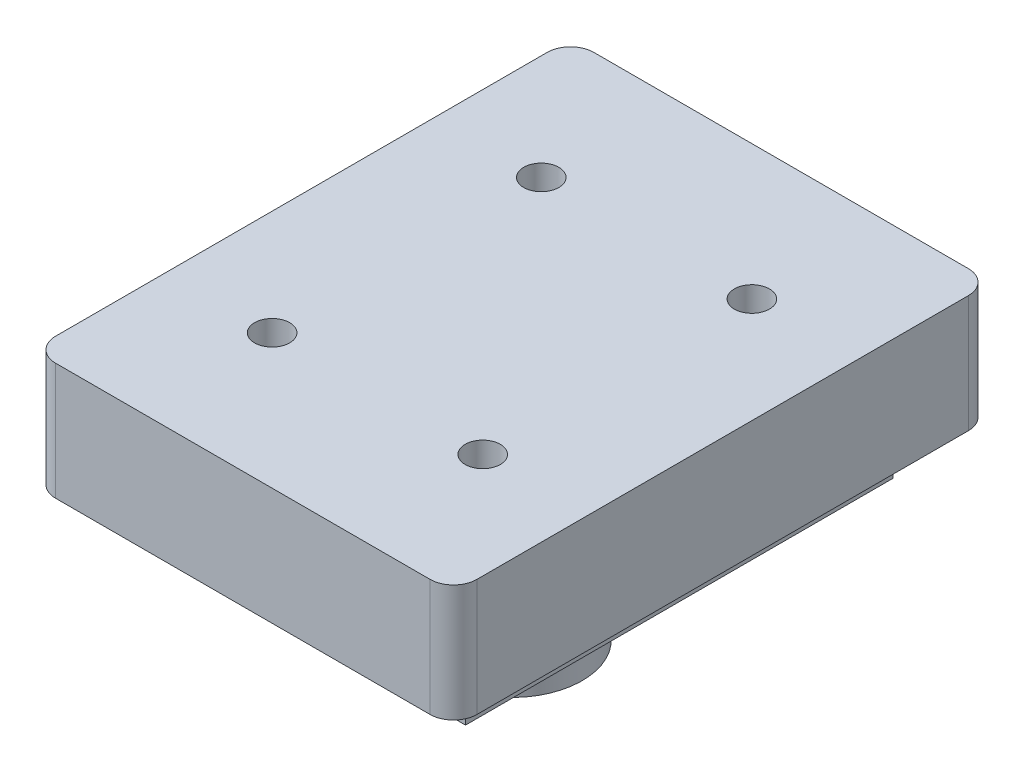
SolidWorks part; units mm, degrees
ref_plane "Front Plane" through (0, 0, 0) normal (0, 0, 1) x (1, 0, 0)
ref_plane "Top Plane" through (0, 0, 0) normal (0, 1, 0) x (1, 0, 0)
ref_plane "Right Plane" through (0, 0, 0) normal (1, 0, 0) x (0, 0, -1)
sketch "Sketch1" plane through (0, 0, 0) normal (0, 1, 0) x (1, 0, 0)
  line L1 (-19.9858, 28.651) -> (25.7342, 28.651)
  line L2 (-19.9858, 28.651) -> (-19.9858, -29.769)
  line L3 (-19.9858, -29.769) -> (25.7342, -29.769)
  line L4 (25.7342, 28.651) -> (25.7342, -29.769)
  dimension "D1" = 58.42
  dimension "D2" = 45.72
extrude "Boss-Extrude1" add sketch "Sketch1" along normal blind 12.7
sketch "Sketch2" plane through (0, 12.7, 0) normal (0, 1, 0) x (1, 0, 0)
  line L1 (25.7342, 28.651) -> (-19.9858, 28.651) construction
  line L3 (-19.9858, -0.559) -> (25.7342, -0.559) construction
  line L4 (-19.9858, 28.651) -> (-19.9858, -29.769) construction
  line L5 (25.7342, -29.769) -> (25.7342, 28.651) construction
  line L9 (-19.9858, -0.559) -> (2.8742, 28.651) construction
  line L10 (2.8742, 28.651) -> (25.7342, -0.559) construction
  circle A0 centre (-8.5558, 14.046) radius 1.905
  circle A1 centre (14.3042, 14.046) radius 1.905
  circle A2 centre (-8.5558, -15.164) radius 1.905
  circle A3 centre (14.3042, -15.164) radius 1.905
  dimension "D2" = 3.81
  dimension "D3" = 3.81
  dimension "D4" = 3.81
  dimension "D5" = 3.81
  dimension "D1" = 18.5459
  dimension "D6" = 29.21
  dimension "D7" = 29.21
  dimension "D8" = 22.86
  dimension "D9" = 22.86
sketch "Sketch3" plane through (0, 0, 0) normal (0, -1, 0) x (1, 0, 0)
  line L1 (-15.2895, 23.7683) -> (21.0379, 23.7683)
  line L2 (-15.2895, 23.7683) -> (-15.2895, -22.6502)
  line L3 (-15.2895, -22.6502) -> (21.0379, -22.6502)
  line L4 (21.0379, 23.7683) -> (21.0379, -22.6502)
  dimension "D1" = 7.62
  dimension "D2" = 7.62
extrude "Cut-Extrude1" cut sketch "Sketch2" against normal through all
extrude "Boss-Extrude2" add sketch "Sketch3" along normal blind 5.08
sketch "Sketch4" plane through (0, -5.08, 0) normal (0, -1, 0) x (1, 0, 0)
  line L0 (-19.9858, 0.559) -> (25.7342, 0.559) construction
  line L1 (-19.9858, -28.651) -> (-19.9858, 29.769) construction
  line L2 (25.7342, 29.769) -> (25.7342, -28.651) construction
  line L3 (2.8742, 29.769) -> (2.8742, -28.651) construction
  line L4 (-19.9858, 29.769) -> (25.7342, 29.769) construction
  line L5 (25.7342, -28.651) -> (-19.9858, -28.651) construction
  circle A0 centre (2.8742, 0.559) radius 7.62
  circle A1 centre (2.8742, 0.559) radius 5.08
  dimension "D1" = 10.16
  dimension "D2" = 15.24
extrude "Boss-Extrude3" add sketch "Sketch4" along normal blind 12.7
fillet "Fillet1" radius 2.54 4 edges at (25.7342, 6.35, -28.651) (-19.9858, 6.35, -28.651) (-19.9858, 6.35, 29.769) (25.7342, 6.35, 29.769)
